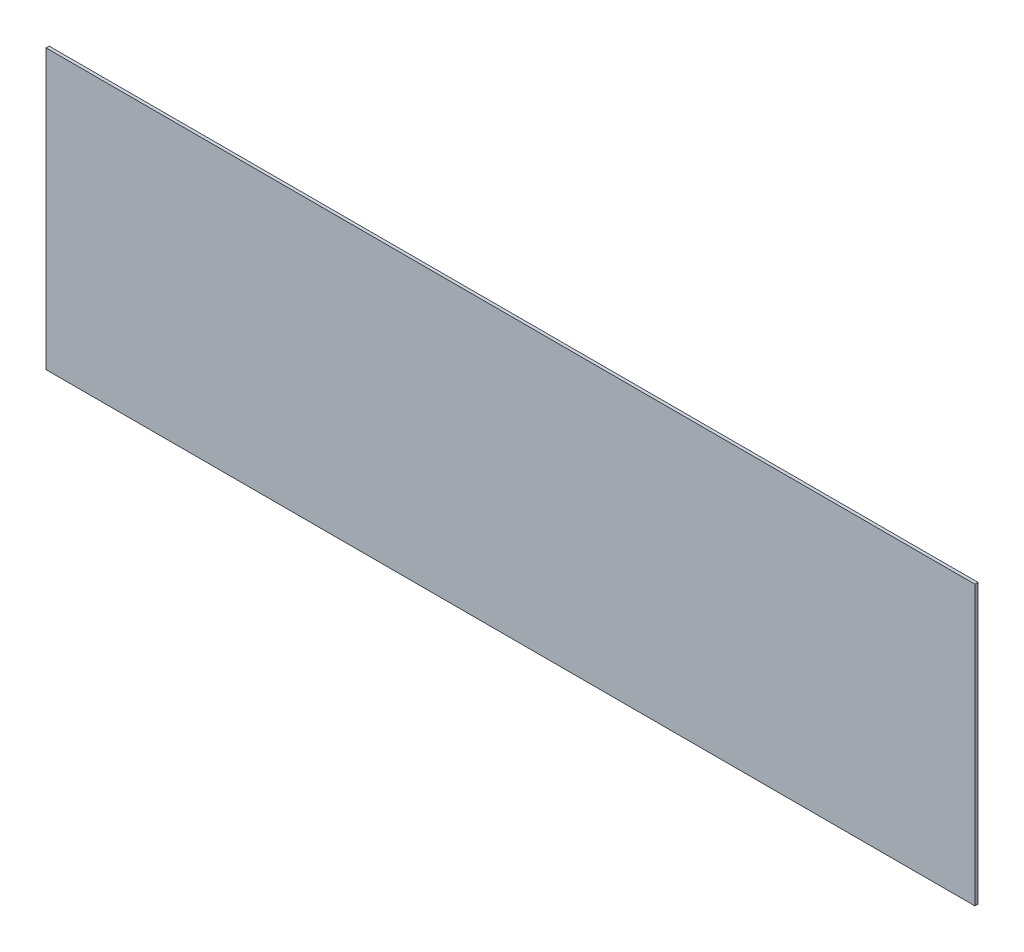
SolidWorks part; units mm, degrees
ref_plane "Front Plane" through (0, 0, 0) normal (0, 0, 1) x (1, 0, 0)
ref_plane "Top Plane" through (0, 0, 0) normal (0, 1, 0) x (1, 0, 0)
ref_plane "Right Plane" through (0, 0, 0) normal (1, 0, 0) x (0, 0, -1)
other "Configuration Table"
sketch "Sketch1" plane through (0, 0, 0) normal (0, 0, 1) x (1, 0, 0)
  line L1 (50, 130) -> (650, 130)
  line L2 (50, 130) -> (50, 310)
  line L3 (50, 310) -> (650, 310)
  line L4 (650, 130) -> (650, 310)
extrude "OVEN_pano_plakasi_1" add sketch "Sketch1" against normal blind 2 from offset 248 separate body
